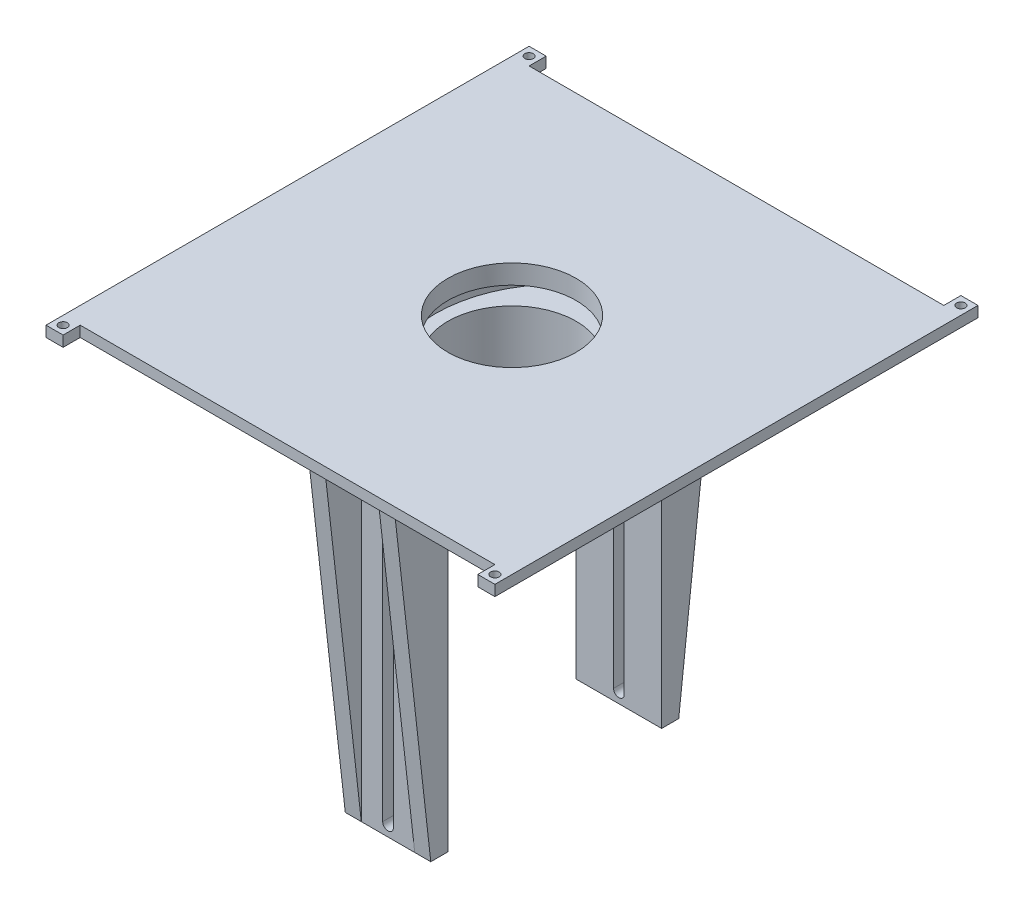
SolidWorks part; units mm, degrees
ref_plane "Front Plane" through (0, 0, 0) normal (0, 0, 1) x (1, 0, 0)
ref_plane "Top Plane" through (0, 0, 0) normal (0, 1, 0) x (1, 0, 0)
ref_plane "Right Plane" through (0, 0, 0) normal (1, 0, 0) x (0, 0, -1)
sketch "Sketch4" plane through (0, 0, 0) normal (0, 1, 0) x (1, 0, 0)
  line L1 (-58, 58) -> (58, 58)
  line L2 (-58, 58) -> (-58, -58)
  line L3 (-58, -58) -> (58, -58)
  line L4 (58, 58) -> (58, -58)
  dimension "D1" = 58
  dimension "D2" = 58
  dimension "D3" = 58
  dimension "D4" = 58
extrude "Boss-Extrude1" add sketch "Sketch4" along normal blind 4
sketch "Sketch6" plane through (0, 4, 0) normal (0, 1, 0) x (1, 0, 0)
  circle A0 centre (0, 0) radius 30
  dimension "D1" = 60
extrude "Cut-Extrude1" cut sketch "Sketch6" against normal through all
sketch "Sketch8" plane through (0, 0, 0) normal (0, -1, 0) x (1, 0, 0)
  line L7 (-58, 58) -> (-58, -58)
  line L8 (22, -58) -> (-58, -58)
  line L9 (58, -58) -> (-58, -58) construction
  line L10 (-58, 58) -> (22, 58)
  line L11 (-58, 58) -> (58, 58) construction
  arc A1 (22, 58) -> (22, -58) centre (22, 0) ccw
  dimension "D3" = 58
  dimension "D1" = 80
  dimension "D2" = 116
extrude "Boss-Extrude3" add sketch "Sketch8" along normal blind 8.4
sketch "Sketch10" plane through (0, -8.4, 0) normal (0, -1, 0) x (1, 0, 0)
  line L1 (-58, 58) -> (58, 58)
  line L2 (-58, 58) -> (-58, -58)
  line L3 (-58, -58) -> (58, -58)
  line L4 (58, 58) -> (58, -58)
extrude "Boss-Extrude5" add sketch "Sketch10" along normal blind 15
sketch "Sketch11" plane through (0, -23.4, 0) normal (0, -1, 0) x (1, 0, 0)
  circle A0 centre (39, 0) radius 4
  dimension "D1" = 8
  dimension "D2" = 39
extrude "positioning hole" cut sketch "Sketch11" against normal blind 26
sketch "Sketch23" plane through (0, -23.4, 0) normal (0, -1, 0) x (1, 0, 0)
  circle A0 centre (38.947, 20) radius 4
  circle A1 centre (39, 0) radius 4 construction
  dimension "D2" = 8
  dimension "D1" = 20
extrude "snapping hole" cut sketch "Sketch23" against normal blind 26
sketch "Sketch13" plane through (0, -23.4, 0) normal (0, -1, 0) x (1, 0, 0)
  circle A0 centre (0, 0) radius 31.25
  circle A1 centre (0, 0) radius 30
  dimension "D1" = 62.5
  dimension "D2" = 60
extrude "Boss-Extrude6" add sketch "Sketch13" along normal blind 25
sketch "Sketch24" plane through (0, -23.4, 0) normal (0, -1, 0) x (1, 0, 0)
  line L0 (58, 58) -> (-58, 58) construction
  line L1 (-20, 58) -> (20, 58)
  line L2 (-20, 58) -> (-20, 50)
  line L3 (-20, 50) -> (20, 50)
  line L4 (20, 58) -> (20, 50)
  line L5 (-58, -58) -> (58, -58) construction
  line L6 (-20, -58) -> (20, -58)
  line L7 (-20, -58) -> (-20, -50)
  line L8 (-20, -50) -> (20, -50)
  line L9 (20, -58) -> (20, -50)
  dimension "D1" = 100
  dimension "D2" = 20
  dimension "D3" = 20
  dimension "D4" = 8
  dimension "D5" = 20
  dimension "D6" = 20
extrude "Boss-Extrude7" add sketch "Sketch24" along normal blind 150
sketch "Sketch28" plane through (-20, 0, 0) normal (-1, 0, 0) x (0, 0, 1)
  line L0 (-58, -173.4) -> (-58, 4)
  line L1 (-58, 4) -> (-78, 4)
  line L2 (-78, 4) -> (-58, -173.4)
  line L3 (58, 4) -> (58, -173.4)
  line L4 (58, -173.4) -> (78, 4)
  line L5 (78, 4) -> (58, 4)
  dimension "D1" = 20
  dimension "D2" = 20
extrude "Boss-Extrude9" add sketch "Sketch28" against normal blind 40
sketch "Sketch31" plane through (0, 0, -58) normal (0, 0, -1) x (-1, 0, 0)
  line L0 (2.5, -28.4) -> (2.5, -168.4)
  line L1 (-2.5, -28.4) -> (-2.5, -168.4)
  line L2 (20, -173.4) -> (-20, -173.4) construction
  line L3 (58, -23.4) -> (20, -23.4) construction
  arc A0 (-2.5, -168.4) -> (2.5, -168.4) centre (0, -168.4) ccw
  arc A1 (-2.5, -28.4) -> (2.5, -28.4) centre (0, -28.4) cw
  dimension "D1" = 5
  dimension "D2" = 2.5
  dimension "D3" = 2.5
  dimension "D4" = 5
extrude "Cut-Extrude6" cut sketch "Sketch31" against normal up to next (8 mm away) and the other way through all
sketch "Sketch34" plane through (0, 0, 50) normal (0, 0, -1) x (-1, 0, 0)
  line L0 (-2.5, -28.4) -> (-2.5, -168.4)
  line L1 (2.5, -28.4) -> (2.5, -168.4)
  arc A0 (-2.5, -168.4) -> (2.5, -168.4) centre (0, -168.4) ccw
  arc A1 (-2.5, -28.4) -> (2.5, -28.4) centre (0, -28.4) cw
extrude "Cut-Extrude7" cut sketch "Sketch34" against normal up to next
sketch "Sketch37" plane through (0, 4, 0) normal (0, 1, 0) x (1, 0, 0)
  line L0 (0, 0) -> (-80.0321, 0) construction
  line L1 (-12.5, 58) -> (12.5, 58)
  line L2 (-12.5, 58) -> (-12.5, 78)
  line L3 (-12.5, 78) -> (12.5, 78)
  line L4 (12.5, 58) -> (12.5, 78)
  line L5 (-80.0321, 0) -> (99.0974, 0) construction
  line L6 (12.5, -58) -> (12.5, -78)
  line L7 (-12.5, -78) -> (12.5, -78)
  line L8 (-12.5, -58) -> (-12.5, -78)
  line L9 (-12.5, -58) -> (12.5, -58)
  line L10 (58, 58) -> (20, 58) construction
  dimension "D1" = 20
  dimension "D2" = 25
  dimension "D3" = 12.5
extrude "Cut-Extrude9" cut sketch "Sketch37" against normal up to next
sketch "Sketch41" plane through (0, 4, 0) normal (0, 1, 0) x (1, 0, 0)
  line L1 (-105, 105) -> (105, 105)
  line L2 (-105, 105) -> (-105, -105)
  line L3 (-105, -105) -> (105, -105)
  line L4 (105, 105) -> (105, -105)
  dimension "D1" = 210
  dimension "D2" = 210
  dimension "D3" = 105
  dimension "D4" = 105
extrude "Boss-Extrude11" add sketch "Sketch41" along normal blind 5
sketch "Sketch12" plane through (0, -23.4, 0) normal (0, -1, 0) x (1, 0, 0)
  circle A0 centre (0, 0) radius 30
  dimension "D1" = 60
extrude "main hole" cut sketch "Sketch12" against normal through all
sketch "Sketch43" plane through (0, 9, 0) normal (0, 1, 0) x (1, 0, 0)
  line L0 (0, 0) -> (-126.9136, 0) construction
  line L1 (105, 105) -> (97, 105)
  line L2 (105, 105) -> (105, 113)
  line L3 (105, 113) -> (97, 113)
  line L4 (97, 105) -> (97, 113)
  line L5 (-105, 105) -> (-97, 105)
  line L6 (-105, 105) -> (-105, 113)
  line L7 (-105, 113) -> (-97, 113)
  line L8 (-97, 105) -> (-97, 113)
  line L9 (-126.9136, 0) -> (147.2198, 0) construction
  line L10 (-97, -105) -> (-97, -113)
  line L11 (-105, -113) -> (-97, -113)
  line L12 (-105, -105) -> (-105, -113)
  line L13 (-105, -105) -> (-97, -105)
  line L14 (97, -105) -> (97, -113)
  line L15 (105, -113) -> (97, -113)
  line L16 (105, -105) -> (105, -113)
  line L17 (105, -105) -> (97, -105)
  circle A0 centre (-101, 109) radius 2
  circle A1 centre (101, 109) radius 2
  circle A2 centre (101, -109) radius 2
  circle A3 centre (-101, -109) radius 2
  dimension "D7" = 4
  dimension "D8" = 4
  dimension "D1" = 8
  dimension "D2" = 8
  dimension "D3" = 8
  dimension "D4" = 8
  dimension "D5" = 4
  dimension "D6" = 4
  dimension "D9" = 4
  dimension "D10" = 4
extrude "Boss-Extrude12" add sketch "Sketch43" against normal blind 5
